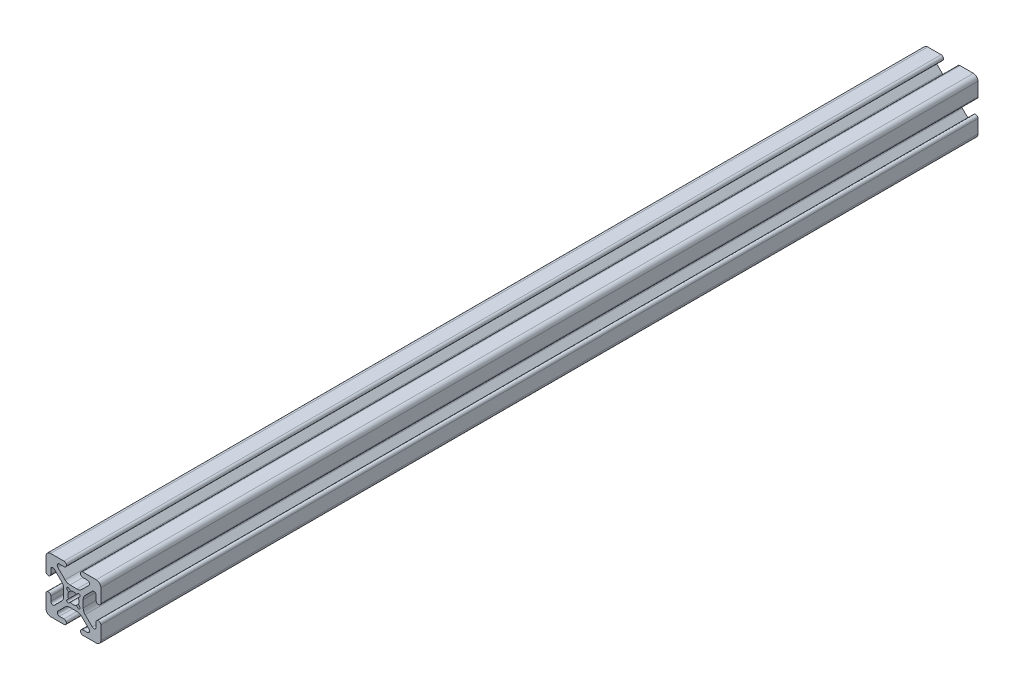
SolidWorks part; units mm, degrees
material "6105-T5 Aluminum"
ref_plane "Front Plane" through (0, 0, 0) normal (0, 0, 1) x (1, 0, 0)
ref_plane "Top Plane" through (0, 0, 0) normal (0, 1, 0) x (1, 0, 0)
ref_plane "Right Plane" through (0, 0, 0) normal (1, 0, 0) x (0, 0, -1)
sketch "Sketch1" plane through (0, 0, 0) normal (0, 0, 1) x (1, 0, 0)
  line L0 (-2.8605, -1.9692) -> (-2.2319, -1.3405)
  line L1 (-2.2319, 1.3405) -> (-2.8605, 1.9692)
  line L2 (-1.9692, 2.8605) -> (-1.3405, 2.2319)
  line L3 (1.3405, 2.2319) -> (1.9692, 2.8605)
  line L4 (2.8605, 1.9692) -> (2.2319, 1.3405)
  line L5 (2.2319, -1.3405) -> (2.8605, -1.9692)
  line L6 (1.9692, -2.8605) -> (1.3405, -2.2319)
  line L7 (-1.3405, -2.2319) -> (-1.9692, -2.8605)
  line L8 (-3.8846, 5.4471) -> (-7.1933, 8.7558)
  line L9 (1.6396, 4.5172) -> (-1.6396, 4.5172)
  line L10 (7.1933, 8.7558) -> (3.8846, 5.4471)
  line L11 (12.7, -10.5918) -> (12.7, -4.3561)
  line L12 (5.4471, 3.8846) -> (8.7558, 7.1933)
  line L13 (4.5172, -1.6396) -> (4.5172, 1.6396)
  line L14 (8.7558, -7.1933) -> (5.4471, -3.8846)
  line L15 (-10.5918, -12.7) -> (-4.3561, -12.7)
  line L16 (3.8846, -5.4471) -> (7.1933, -8.7558)
  line L17 (-1.6396, -4.5172) -> (1.6396, -4.5172)
  line L18 (-7.1933, -8.7558) -> (-3.8846, -5.4471)
  line L19 (-12.7, 10.5918) -> (-12.7, 4.3561)
  line L20 (-5.4471, -3.8846) -> (-8.7558, -7.1933)
  line L21 (-4.5172, 1.6396) -> (-4.5172, -1.6396)
  line L22 (-8.7558, 7.1933) -> (-5.4471, 3.8846)
  line L23 (-10.5918, 12.7) -> (-4.3561, 12.7)
  line L24 (-6.4749, 10.4902) -> (-4.3561, 10.4902)
  line L25 (-10.4902, 6.4749) -> (-10.4902, 4.3561)
  line L26 (-6.4749, -10.4902) -> (-4.3561, -10.4902)
  line L27 (10.4902, -6.4749) -> (10.4902, -4.3561)
  line L28 (4.3561, 12.7) -> (10.5918, 12.7)
  line L29 (4.3561, 10.4902) -> (6.4749, 10.4902)
  line L30 (-10.4902, -4.3561) -> (-10.4902, -6.4749)
  line L31 (-12.7, -4.3561) -> (-12.7, -10.5918)
  line L32 (4.3561, -10.4902) -> (6.4749, -10.4902)
  line L33 (4.3561, -12.7) -> (10.5918, -12.7)
  line L34 (12.7, 4.3561) -> (12.7, 10.5918)
  line L35 (10.4902, 4.3561) -> (10.4902, 6.4749)
  arc A0 (-2.8605, -1.9692) -> (-1.9692, -2.8605) centre (-2.4696, -2.4696) ccw
  arc A1 (-2.2319, 1.3405) -> (-2.2319, -1.3405) centre (0, 0) ccw
  arc A2 (-1.9692, 2.8605) -> (-2.8605, 1.9692) centre (-2.4696, 2.4696) ccw
  arc A3 (1.3405, 2.2319) -> (-1.3405, 2.2319) centre (0, 0) ccw
  arc A4 (2.8605, 1.9692) -> (1.9692, 2.8605) centre (2.4696, 2.4696) ccw
  arc A5 (2.2319, -1.3405) -> (2.2319, 1.3405) centre (0, 0) ccw
  arc A6 (1.9692, -2.8605) -> (2.8605, -1.9692) centre (2.4696, -2.4696) ccw
  arc A7 (-1.3405, -2.2319) -> (1.3405, -2.2319) centre (0, 0) ccw
  arc A8 (-3.8846, 5.4471) -> (-1.6396, 4.5172) centre (-1.6396, 7.6922) ccw
  arc A9 (1.6396, 4.5172) -> (3.8846, 5.4471) centre (1.6396, 7.6922) ccw
  arc A10 (5.4471, 3.8846) -> (4.5172, 1.6396) centre (7.6922, 1.6396) ccw
  arc A11 (4.5172, -1.6396) -> (5.4471, -3.8846) centre (7.6922, -1.6396) ccw
  arc A12 (3.8846, -5.4471) -> (1.6396, -4.5172) centre (1.6396, -7.6922) ccw
  arc A13 (-1.6396, -4.5172) -> (-3.8846, -5.4471) centre (-1.6396, -7.6922) ccw
  arc A14 (-5.4471, -3.8846) -> (-4.5172, -1.6396) centre (-7.6922, -1.6396) ccw
  arc A15 (-4.5172, 1.6396) -> (-5.4471, 3.8846) centre (-7.6922, 1.6396) ccw
  arc A16 (-12.7, -10.5918) -> (-10.5918, -12.7) centre (-10.5918, -10.5918) ccw
  arc A17 (10.5918, -12.7) -> (12.7, -10.5918) centre (10.5918, -10.5918) ccw
  arc A18 (12.7, 10.5918) -> (10.5918, 12.7) centre (10.5918, 10.5918) ccw
  arc A19 (-10.5918, 12.7) -> (-12.7, 10.5918) centre (-10.5918, 10.5918) ccw
  arc A20 (-8.7558, 7.1933) -> (-10.4902, 6.4749) centre (-9.4742, 6.4749) ccw
  arc A21 (-6.4749, 10.4902) -> (-7.1933, 8.7558) centre (-6.4749, 9.4742) ccw
  arc A22 (7.1933, 8.7558) -> (6.4749, 10.4902) centre (6.4749, 9.4742) ccw
  arc A23 (10.4902, 6.4749) -> (8.7558, 7.1933) centre (9.4742, 6.4749) ccw
  arc A24 (8.7558, -7.1933) -> (10.4902, -6.4749) centre (9.4742, -6.4749) ccw
  arc A25 (6.4749, -10.4902) -> (7.1933, -8.7558) centre (6.4749, -9.4742) ccw
  arc A26 (-7.1933, -8.7558) -> (-6.4749, -10.4902) centre (-6.4749, -9.4742) ccw
  arc A27 (-10.4902, -6.4749) -> (-8.7558, -7.1933) centre (-9.4742, -6.4749) ccw
  arc A28 (-4.3561, 10.4902) -> (-4.3561, 12.7) centre (-4.3561, 11.5951) ccw
  arc A29 (4.3561, 12.7) -> (4.3561, 10.4902) centre (4.3561, 11.5951) ccw
  arc A30 (-12.7, 4.3561) -> (-10.4902, 4.3561) centre (-11.5951, 4.3561) ccw
  arc A31 (-10.4902, -4.3561) -> (-12.7, -4.3561) centre (-11.5951, -4.3561) ccw
  arc A32 (-4.3561, -12.7) -> (-4.3561, -10.4902) centre (-4.3561, -11.5951) ccw
  arc A33 (4.3561, -10.4902) -> (4.3561, -12.7) centre (4.3561, -11.5951) ccw
  arc A34 (12.7, -4.3561) -> (10.4902, -4.3561) centre (11.5951, -4.3561) ccw
  arc A35 (10.4902, 4.3561) -> (12.7, 4.3561) centre (11.5951, 4.3561) ccw
extrude "Extrude1" add sketch "Sketch1" against normal blind 406.4
